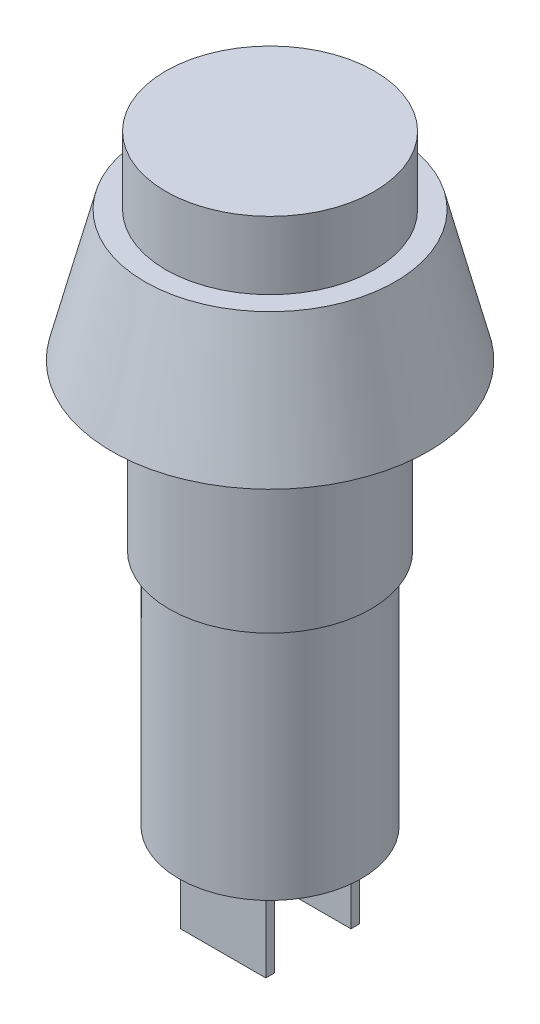
SolidWorks part; units mm, degrees
ref_plane "Спереди" through (0, 0, 0) normal (0, 0, 1) x (1, 0, 0)
ref_plane "Сверху" through (0, 0, 0) normal (0, 1, 0) x (1, 0, 0)
ref_plane "Справа" through (0, 0, 0) normal (1, 0, 0) x (0, 0, -1)
sketch "Эскиз1" plane through (0, 0, 0) normal (0, 1, 0) x (1, 0, 0)
  circle A0 centre (0, 0) radius 9.1
  circle A1 centre (0, 0) radius 7.2
sketch "Эскиз5" plane through (0, 0, 0) normal (0, 0, 1) x (1, 0, 0)
  line L0 (0, 0) -> (-9.1, 0) construction
  line L1 (7.2, 0) -> (-7.2, 0) construction
  line L2 (9.1, 0) -> (-9.1, 0) construction
  line L3 (-9.1, 0) -> (-7.2, 0) construction
  line L4 (-9.1, 0) -> (-9.1, 7.5) construction
  line L5 (-7.2, 0) -> (-7.2, 7.5) construction
  line L6 (-7.2, 7.5) -> (-9.1, 0)
  line L7 (0, 0) -> (0, 7.5) construction
  line L8 (0, 0) -> (0, 7.5)
  line L9 (0, 7.5) -> (-7.2, 7.5)
  line L10 (-9.1, 0) -> (0, 0)
revolve "Повернуть1" add sketch "Эскиз5" angle 360 about L8
sketch "Эскиз6" plane through (0, 7.5, 0) normal (0, 1, 0) x (1, 0, 0)
  circle A0 centre (0, 0) radius 6
extrude "Бобышка-Вытянуть3" add sketch "Эскиз6" along normal blind 3.9 contours A0
sketch "Эскиз7" plane through (0, 0, 0) normal (0, -1, 0) x (1, 0, 0)
  circle A0 centre (0, 0) radius 5.8
extrude "Бобышка-Вытянуть4" add sketch "Эскиз7" along normal blind 9.5
sketch "Эскиз8" plane through (0, -9.5, 0) normal (0, -1, 0) x (1, 0, 0)
  circle A0 centre (0, 0) radius 5.25
extrude "Бобышка-Вытянуть5" add sketch "Эскиз8" along normal blind 13.7
sketch "Эскиз9" plane through (0, -23.2, 0) normal (0, -1, 0) x (-1, 0, 0)
  line L0 (0, 0) -> (0, 2.2) construction
  line L1 (0, 0) -> (0, -2.2) construction
  line L2 (0, 2.2) -> (2.4489, 2.2) construction
  line L3 (0, -2.2) -> (2.4489, -2.2) construction
  line L4 (2.4489, 2.2) -> (-2.4497, 2.2)
  line L5 (2.4489, 2.2) -> (2.4489, 2.7004)
  line L6 (2.4489, 2.7004) -> (-2.4497, 2.7004)
  line L7 (-2.4497, 2.2) -> (-2.4497, 2.7004)
  line L9 (2.4489, -2.2) -> (-2.4497, -2.2)
  line L10 (2.4489, -2.2) -> (2.4489, -2.6956)
  line L11 (2.4489, -2.6956) -> (-2.4497, -2.6956)
  line L12 (-2.4497, -2.2) -> (-2.4497, -2.6956)
extrude "Бобышка-Вытянуть6" add sketch "Эскиз9" along normal blind 5
